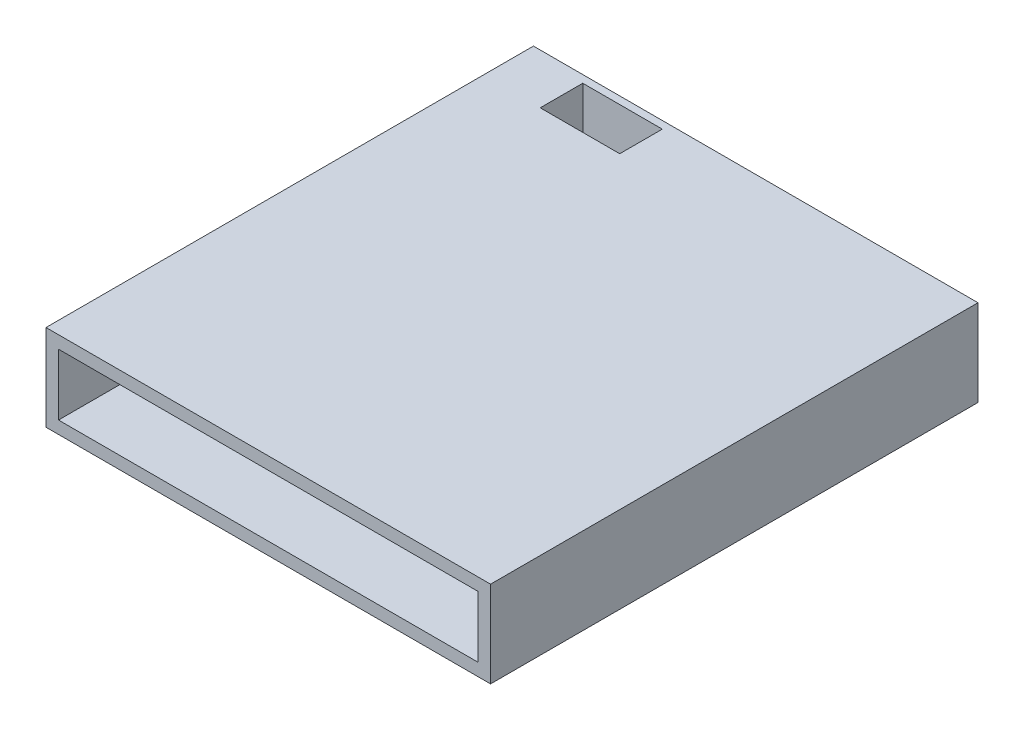
SolidWorks part; units mm, degrees
ref_plane "Front Plane" through (0, 0, 0) normal (0, 0, 1) x (1, 0, 0)
ref_plane "Top Plane" through (0, 0, 0) normal (0, 1, 0) x (1, 0, 0)
ref_plane "Right Plane" through (0, 0, 0) normal (1, 0, 0) x (0, 0, -1)
sketch "Sketch1" plane through (0, 0, 0) normal (0, 0, 1) x (1, 0, 0)
  line L1 (-0.25, -0.25) -> (66.75, -0.25)
  line L2 (-0.25, -0.25) -> (-0.25, 9.55)
  line L3 (-0.25, 9.55) -> (66.75, 9.55)
  line L4 (66.75, -0.25) -> (66.75, 9.55)
  point P4 (0, 0)
  point P5 (66.75, 9.55)
  point P6 (0, 0)
  point P8 (-0.25, 9.55)
  point P9 (-0.25, -0.25)
  point P10 (0, 0)
  point P11 (66.8977, 9.55)
  point P12 (66.75, -0.25)
  point P13 (0, 0)
extrude "Extrude-Thin1" add sketch "Sketch1" along normal blind 69.85 thin
sketch "Sketch5" plane through (0, 0, 0) normal (0, 1, 0) x (1, 0, 0)
  line L1 (-2.25, 0) -> (68.75, 0)
  line L2 (-2.25, 0) -> (-2.25, 8)
  line L3 (-2.25, 8) -> (68.75, 8)
  line L4 (68.75, 0) -> (68.75, 8)
  point P5 (68.75, 0)
extrude "Boss-Extrude2" add sketch "Sketch5" along normal up to vertex (11.55 mm away) and the other way up to vertex (2.25 mm away) up to point (-2.25, 11.55, 0) other way up to point (-2.25, -2.25, 0)
sketch "Sketch6" plane through (0, 0, 0) normal (0, 0, 1) x (1, 0, 0)
  line L7 (6.83, 11.9163) -> (19.53, 11.9163)
  line L8 (6.83, 11.9163) -> (6.83, 2.06)
  line L9 (6.83, 2.06) -> (19.53, 2.06)
  line L10 (19.53, 11.9163) -> (19.53, 2.06)
  point P2 (0, 0)
  point P3 (0, 0)
  point P4 (0, 0)
  point P5 (6.9828, 2.06)
  point P6 (19.3724, 2.06)
  point P7 (0, 0)
  point P10 (19.3724, 11.9163)
  point P12 (6.9828, 11.9163)
extrude "Cut-Extrude1" cut sketch "Sketch6" against normal blind 6.8
